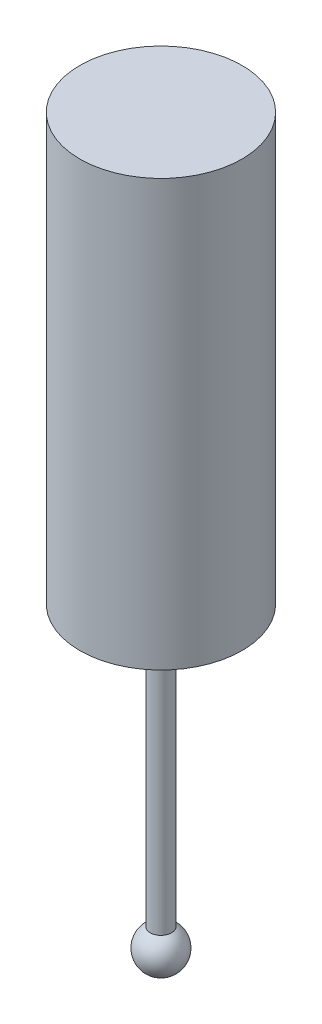
SolidWorks part; units mm, degrees
ref_plane "Front Plane" through (0, 0, 0) normal (0, 0, 1) x (1, 0, 0)
ref_plane "Top Plane" through (0, 0, 0) normal (0, 1, 0) x (1, 0, 0)
ref_plane "Right Plane" through (0, 0, 0) normal (1, 0, 0) x (0, 0, -1)
ref_plane "Plane1" through (0, 70, 0) normal (0, 1, 0) x (-1, 0, 0)
sketch "Sketch1" plane through (0, 70, 0) normal (0, 1, 0) x (-1, 0, 0)
  circle A0 centre (0, 0) radius 19.05
  dimension "D1" = 38.1
extrude "Boss-Extrude1" add sketch "Sketch1" along normal blind 100
sketch "Sketch2" plane through (0, 0, 0) normal (0, 1, 0) x (1, 0, 0)
  line L0 (-5, 0) -> (5, 0)
  arc A0 (-5, 0) -> (5, 0) centre (0, 0) ccw
  dimension "D1" = 5
revolve "Revolve1" add sketch "Sketch2" angle 360 about L0
sketch "Sketch3" plane through (0, 70, 0) normal (0, -1, 0) x (1, 0, 0)
  circle A0 centre (0, 0) radius 2.5
  dimension "D1" = 5
extrude "Boss-Extrude2" add sketch "Sketch3" along normal up to next
